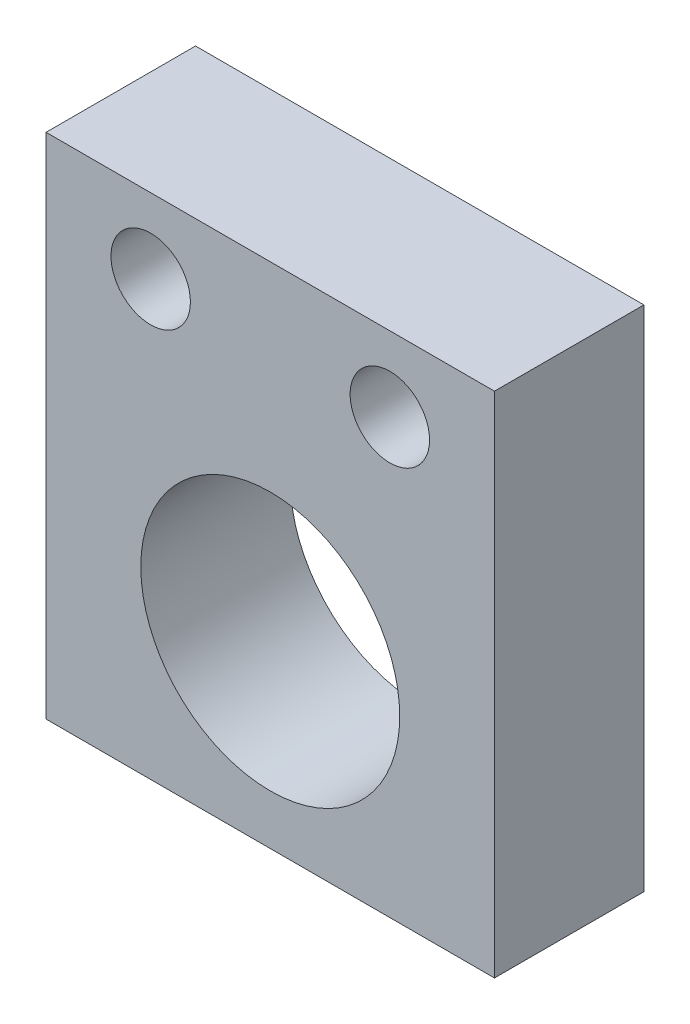
SolidWorks part; units mm, degrees
material "6063-T5"
ref_plane "Front Plane" through (0, 0, 0) normal (0, 0, 1) x (1, 0, 0)
ref_plane "Top Plane" through (0, 0, 0) normal (0, 1, 0) x (1, 0, 0)
ref_plane "Right Plane" through (0, 0, 0) normal (1, 0, 0) x (0, 0, -1)
sketch "Sketch1" plane through (0, 0, 0) normal (0, 0, 1) x (1, 0, 0)
  line L1 (0, 0) -> (38.1, 0)
  line L2 (0, 0) -> (0, 43.18)
  line L3 (0, 43.18) -> (38.1, 43.18)
  line L4 (38.1, 0) -> (38.1, 43.18)
  dimension "D1" = 38.1
  dimension "D2" = 43.18
extrude "Boss-Extrude1" add sketch "Sketch1" against normal blind 12.7
sketch "Sketch3" plane through (0, 0, 0) normal (0, 0, 1) x (1, 0, 0)
  line L0 (19.05, -987.2485) -> (19.05, 49012.7515) construction
  line L1 (0, 43.18) -> (0, 0) construction
  line L2 (38.1, 0) -> (38.1, 43.18) construction
  line L3 (38.1, 43.18) -> (0, 43.18) construction
  circle A0 centre (19.05, 15.24) radius 11
  dimension "D1" = 27.94
extrude "Cut-Extrude1" cut sketch "Sketch3" against normal through all contours A0
sketch "Sketch5" plane through (0, 0, 0) normal (0, 0, 1) x (1, 0, 0)
  line L0 (19.05, -968.1712) -> (19.05, 49031.8288) construction
  line L1 (0, 43.18) -> (0, 0) construction
  line L2 (38.1, 0) -> (38.1, 43.18) construction
  line L3 (38.1, 43.18) -> (0, 43.18) construction
  point P6 (8.89, 36.83)
  point P7 (29.21, 36.83)
  dimension "D1" = 20.32
  dimension "D2" = 6.35
hole_wizard "17/64 (0.26563) Diameter Hole1" positions "3DSketch2" profile "Sketch7" hole size "17/64" standard "ANSI Inch" end condition through all
sketch3d "3DSketch2"
  point P0 (29.21, 36.83, 0)
  point P3 (8.89, 36.83, 0)
sketch "Sketch7" plane through (29.21, 36.83, 0) normal (1, 0, 0) x (0, -1, 0)
  line L0 (0, 0) -> (0, 12.7)
  line L1 (0, 12.7) -> (3.3735, 12.7)
  line L2 (3.3735, 12.7) -> (3.3735, 0)
  line L5 (3.3735, 0) -> (0, 0)
  line L11 (0, -6.35) -> (0, 107.95) construction
  dimension "Thru Hole Dia." = 6.747
  dimension "Thru Hole Depth" = 12.7
